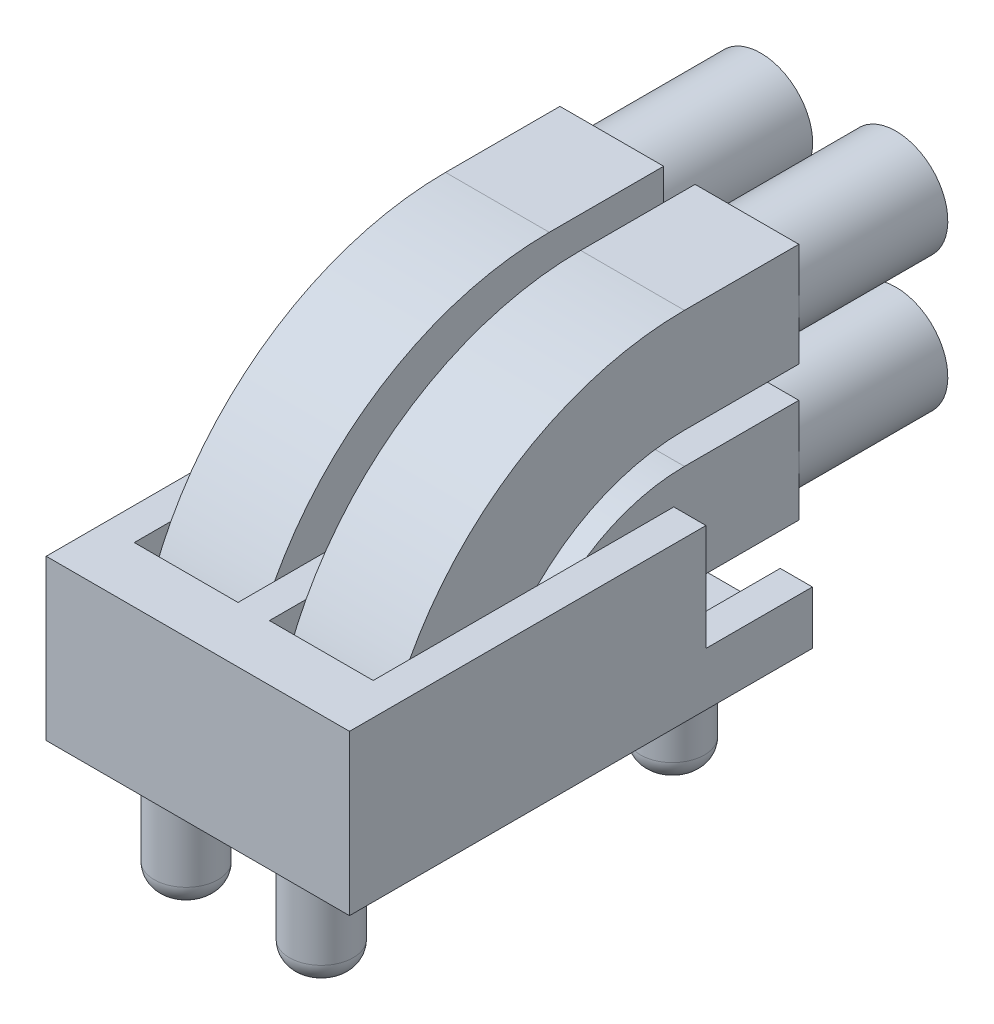
SolidWorks part; units mm, degrees
ref_plane "Płaszczyzna przednia" through (0, 0, 0) normal (0, 0, 1) x (1, 0, 0)
ref_plane "Płaszczyzna górna" through (0, 0, 0) normal (0, 1, 0) x (1, 0, 0)
ref_plane "Płaszczyzna prawa" through (0, 0, 0) normal (1, 0, 0) x (0, 0, -1)
sketch "Szkic1" plane through (0, 0, 0) normal (0, 1, 0) x (1, 0, 0)
  line L1 (-2.85, 4.35) -> (2.85, 4.35)
  line L2 (-2.85, 4.35) -> (-2.85, -4.35)
  line L3 (-2.85, -4.35) -> (2.85, -4.35)
  line L4 (2.85, 4.35) -> (2.85, -4.35)
  line L5 (-2.85, 4.35) -> (2.85, -4.35) construction
  line L6 (-2.85, -4.35) -> (2.85, 4.35) construction
  point P0 (0, 0)
  dimension "D1" = 5.7
  dimension "D2" = 8.7
extrude "Dodanie-wyciągnięcie1" add sketch "Szkic1" along normal blind 3
sketch "Szkic5" plane through (0, 3, 0) normal (0, 1, 0) x (1, 0, 0)
  line L0 (2.85, 4.35) -> (-2.85, 4.35) construction
  line L1 (2.245, 4.35) -> (0.295, 4.35)
  line L2 (2.245, 4.35) -> (2.245, -3.3)
  line L3 (2.245, -3.3) -> (0.295, -3.3)
  line L4 (0.295, 4.35) -> (0.295, -3.3)
  line L5 (2.85, -4.35) -> (2.85, 4.35) construction
  line L6 (-0.295, 4.35) -> (-2.245, 4.35)
  line L7 (-0.295, 4.35) -> (-0.295, -3.3)
  line L8 (-0.295, -3.3) -> (-2.245, -3.3)
  line L9 (-2.245, 4.35) -> (-2.245, -3.3)
  line L10 (-2.85, -4.35) -> (2.85, -4.35) construction
  dimension "D1" = 1.95
  dimension "D2" = 1.95
  dimension "D3" = 0.605
  dimension "D4" = 2.54
  dimension "D5" = 1.05
  dimension "D6" = 1.05
extrude "Wytnij-wyciągnięcie2" cut sketch "Szkic5" against normal blind 2.75
sketch "Szkic3" plane through (2.85, 0, 1.65) normal (-1, 0, 0) x (0, 0, 1)
  line L1 (-6, 3) -> (-4, 3)
  line L6 (-6, 3) -> (-6, 1)
  line L7 (-6, 1) -> (-4, 1)
  line L8 (-4, 3) -> (-4, 1)
  dimension "D1" = 2
  dimension "D2" = 2
extrude "Wytnij-wyciągnięcie1" cut sketch "Szkic3" along normal through all
sketch "Szkic6" plane through (0, 0, 0) normal (0, -1, 0) x (1, 0, 0)
  line L0 (0, -4.35) -> (0, 4.35) construction
  line L1 (2.85, -4.35) -> (-2.85, -4.35) construction
  line L2 (-2.85, 4.35) -> (2.85, 4.35) construction
  line L3 (2.85, 0) -> (-2.85, 0) construction
  line L4 (2.85, 4.35) -> (2.85, -4.35) construction
  line L5 (-2.85, -4.35) -> (-2.85, 4.35) construction
  circle A0 centre (1.27, 3.3) radius 0.6
  circle A1 centre (-1.27, 3.3) radius 0.6
  circle A2 centre (1.27, -3.3) radius 0.6
  circle A3 centre (-1.27, -3.3) radius 0.6
  dimension "D1" = 1.2
  dimension "D2" = 1.2
  dimension "D3" = 1.2
  dimension "D4" = 1.2
  dimension "D5" = 2.54
  dimension "D6" = 6.6
  dimension "D8" = 6.6
extrude "Dodanie-wyciągnięcie2" add sketch "Szkic6" along normal blind 2.1
fillet "Zaokrąglenie1" radius 0.4 4 edges at (-1.27, -2.1, -3.9) (1.27, -2.1, -3.9) (-1.27, -2.1, 2.7) (1.27, -2.1, 2.7)
sketch "Szkic7" plane through (0.295, 0, 0) normal (1, 0, 0) x (0, 0, -1)
  line L0 (4.35, 0.25) -> (-3.3, 0.25) construction
  line L1 (-4.35, 3) -> (-4.35, 0) construction
  line L2 (2.55, 6.1) -> (7.5, 6.1)
  line L4 (2.55, 4.15) -> (7.5, 4.15)
  line L5 (7.5, 6.1) -> (7.5, 4.15)
  line L6 (-3.3, 0.25) -> (-1.35, 0.25)
  arc A0 (-3.3, 0.25) -> (2.55, 6.1) centre (2.55, 0.25) cw
  arc A1 (2.55, 4.15) -> (-1.35, 0.25) centre (2.55, 0.25) ccw
  dimension "D1" = 5.85
  dimension "D2" = 5.85
  dimension "D3" = 1.95
  dimension "D4" = 11.85
extrude "Dodanie-wyciągnięcie3" add sketch "Szkic7" along normal up to surface (1.95 mm away) up to face at (2.245, 1.4167, -1.1333)
sketch "Szkic8" plane through (0.295, 0, 0) normal (1, 0, 0) x (0, 0, -1)
  line L0 (7.5, 6.1) -> (2.55, 6.1) construction
  line L1 (4.35, 0.25) -> (-1.35, 0.25) construction
  line L2 (7.5, 3.56) -> (2.55, 3.56)
  line L3 (7.5, 3.56) -> (7.5, 1.61)
  line L4 (7.5, 1.61) -> (2.55, 1.61)
  line L6 (1.19, 0.25) -> (-0.76, 0.25)
  line L7 (7.5, 4.15) -> (7.5, 6.1) construction
  arc A0 (2.55, 3.56) -> (-0.76, 0.25) centre (2.55, 0.25) ccw
  arc A1 (2.55, 1.61) -> (1.19, 0.25) centre (2.55, 0.25) ccw
  point P7 (2.55, 0.25)
  dimension "D1" = 2.54
  dimension "D2" = 1.95
extrude "Dodanie-wyciągnięcie4" add sketch "Szkic8" along normal up to surface (1.95 mm away) up to face at (2.245, 1.4354, -1.927)
ref_plane "Płaszczyzna1" through (0, 0, 0) normal (-1, 0, 0) x (0, 0, 1)
mirror "Lustro2" about plane through (0, 0, 0) normal (-1, 0, 0) of "Dodanie-wyciągnięcie4", "Dodanie-wyciągnięcie3"
sketch "Szkic9" plane through (0, 0, -7.5) normal (0, 0, -1) x (-1, 0, 0)
  line L0 (-2.85, 0) -> (2.85, 0) construction
  line L2 (0.295, 6.1) -> (-0.295, 6.1) construction
  line L3 (0, 6.1) -> (0, 8.8173) construction
  circle A0 centre (-1.27, 2.54) radius 0.975
  circle A1 centre (-1.27, 5.08) radius 0.975
  circle A2 centre (1.27, 5.08) radius 0.975
  circle A3 centre (1.27, 2.54) radius 0.975
  dimension "D1" = 1.95
  dimension "D2" = 1.95
  dimension "D3" = 1.95
  dimension "D4" = 1.95
  dimension "D5" = 2.54
  dimension "D6" = 2.54
  dimension "D7" = 2.54
extrude "Wytnij-wyciągnięcie4" cut sketch "Szkic9" against normal blind 2.8 flip side to cut
